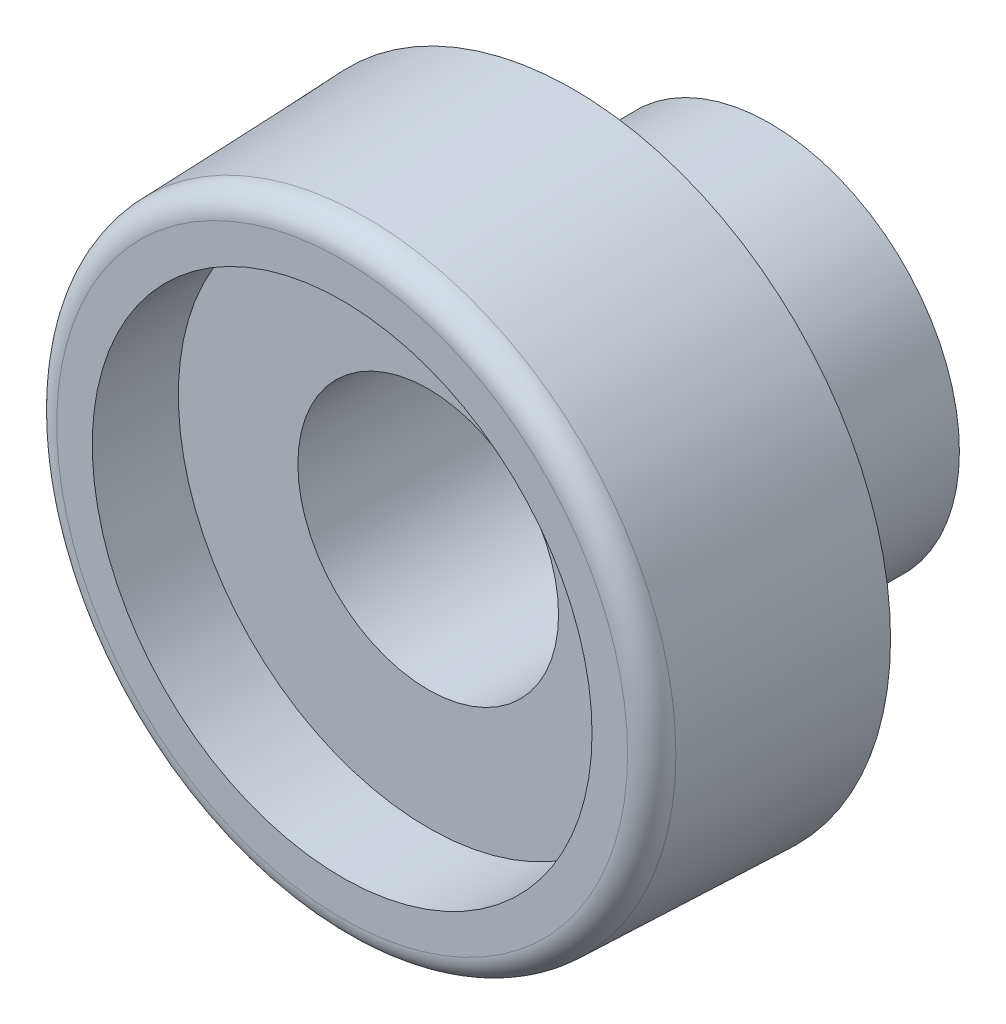
SolidWorks part; units mm, degrees
ref_plane "Plan de face" through (0, 0, 0) normal (0, 0, 1) x (1, 0, 0)
ref_plane "Plan de dessus" through (0, 0, 0) normal (0, 1, 0) x (1, 0, 0)
ref_plane "Plan de droite" through (0, 0, 0) normal (1, 0, 0) x (0, 0, -1)
sketch "Esquisse1" plane through (0, 0, 0) normal (0, 0, 1) x (1, 0, 0)
  circle A0 centre (0, 0) radius 6.45
  circle A1 centre (0, 0) radius 5.15
  dimension "D1" = 12.9
  dimension "D2" = 10.3
extrude "Boss.-Extru.1" add sketch "Esquisse1" along normal blind 4.7 draft 2
sketch "Esquisse2" plane through (0, 0, 4.7) normal (0, 0, 1) x (1, 0, 0)
  circle A0 centre (0, 0) radius 6.2859
  circle A1 centre (0, 0) radius 2.65
  dimension "D1" = 5.3
extrude "Boss.-Extru.2" add sketch "Esquisse2" against normal blind 4.7
fillet "Congé1" radius 0.5 1 edges at (6.2859, 0, 4.7)
sketch "Esquisse3" plane through (0, 0, 0) normal (0, 0, -1) x (-1, 0, 0)
  circle A0 centre (0, 0) radius 6.45
  circle A1 centre (0, 0) radius 3.85
  circle A2 centre (0, 0) radius 2.65
  circle A3 centre (0, 0) radius 2.65 construction
  circle A4 centre (0, 0) radius 2.65
  circle M6 centre (0, 0) radius 2.65
  dimension "D1" = 7.7
sketch "Esquisse4" plane through (0, 0, 4.7) normal (0, 0, 1) x (1, 0, 0)
  circle A0 centre (0, 0) radius 5.0807
extrude "Enlèv. mat.-Extru.1" cut sketch "Esquisse4" against normal blind 1.75
extrude "Boss.-Extru.8" add sketch "Esquisse3" along normal blind 4 contours A1 M6
